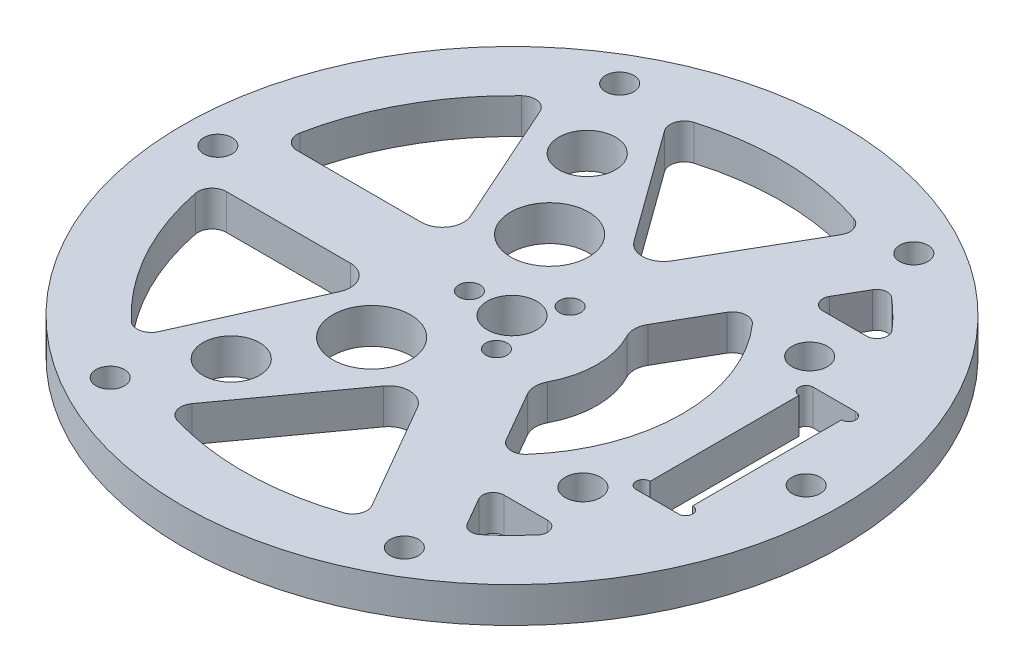
SolidWorks part; units mm, degrees
material "Thornel Mat VMA"
ref_plane "前视基准面" through (0, 0, 0) normal (0, 0, 1) x (1, 0, 0)
ref_plane "上视基准面" through (0, 0, 0) normal (0, 1, 0) x (1, 0, 0)
ref_plane "右视基准面" through (0, 0, 0) normal (1, 0, 0) x (0, 0, -1)
sketch "草图1" plane through (0, 0, 0) normal (0, 1, 0) x (1, 0, 0)
  line L7 (0, 0) -> (36, 0) construction
  line L8 (26, 16) -> (26, -16) construction
  line L11 (30, 12.5) -> (30, -12.5)
  line L12 (30, -12.5) -> (36, -12.5)
  line L13 (36, -12.5) -> (36, 12.5)
  line L14 (36, 12.5) -> (30, 12.5)
  circle A0 centre (0, 0) radius 41.5 construction
  circle A1 centre (0, 0) radius 46.5
  circle A2 centre (-20.75, 35.9401) radius 2
  circle A3 centre (20.75, 35.9401) radius 2
  circle A4 centre (41.5, 0) radius 2
  circle A5 centre (20.75, -35.9401) radius 2
  circle A6 centre (0, 0) radius 3.5
  circle A7 centre (-20.75, -35.9401) radius 2
  circle A8 centre (-41.5, 0) radius 2
  circle A9 centre (26, 16) radius 2.5
  circle A10 centre (26, -16) radius 2.5
  circle A12 centre (-14.5, 25.1147) radius 4
  circle A13 centre (0, 0) radius 6 construction
  circle A14 centre (-6, 0) radius 1.5
  circle A15 centre (3, 5.1962) radius 1.5
  circle A16 centre (29, 0) radius 4 construction
  circle A17 centre (3, -5.1962) radius 1.5
  circle A18 centre (-14.5, -25.1147) radius 4
  circle A19 centre (0, 0) radius 29 construction
  point P24 (26, 0)
  dimension "D1" = 5
  dimension "D2" = 4
  dimension "D3" = 83
  dimension "D4" = 6
  dimension "D9" = 5
  dimension "D11" = 7
  dimension "D12" = 12
  dimension "D13" = 3
  dimension "D15" = 58
  dimension "D16" = 8
  dimension "D6" = 25
  dimension "D7" = 30
  dimension "D8" = 4
  dimension "D10" = 32
  dimension "D5" = 6
  dimension "D14" = 3
extrude "凸台-拉伸1" add sketch "草图1" along normal blind 5
hole_wizard "孔1" positions "草图2" profile "草图3" legacy end condition through all
sketch "草图2" plane through (0, 0, 0) normal (0, -1, 0) x (-1, 0, 0)
  point P2 (-3, 5.1962)
  point P11 (6, 0)
  point P12 (-3, -5.1962)
  point P14 (6, -0.4384)
  point P15 (6, 0)
  dimension "D1" = 3
sketch "草图3" plane through (3, 0, -5.1962) normal (1, 0, 0) x (0, 0, -1)
  line L0 (0, 0) -> (0, 5)
  line L1 (0, 5) -> (1.5, 5)
  line L2 (1.5, 5) -> (1.5, 1.5)
  line L3 (1.5, 1.5) -> (3, 0)
  line L4 (3, 0) -> (0, 0)
  line L5 (0, -6.4453) -> (0, 115.525) construction
  line L6 (-1.5, 1.5) -> (-3, 0) construction
  dimension "直径" = 3
  dimension "深度" = 5
  dimension "锥坑角度" = 90
  dimension "锥坑直径" = 6
hole_wizard "孔2" positions "草图6" profile "草图7" legacy end condition through all
sketch "草图6" plane through (0, 0, 0) normal (0, -1, 0) x (-1, 0, 0)
  point P0 (-41.5, 0)
  point P7 (-20.75, 35.9401)
  point P8 (20.75, 35.9401)
  point P9 (41.5, 0)
  point P10 (20.75, -35.9401)
  point P11 (-20.75, -35.9401)
  point P13 (-20.75, 35.9401)
  dimension "D1" = 6
sketch "草图7" plane through (41.5, 0, 0) normal (1, 0, 0) x (0, 0, -1)
  line L0 (0, 0) -> (0, 5)
  line L1 (0, 5) -> (2, 5)
  line L2 (2, 5) -> (2, 2)
  line L3 (2, 2) -> (4, 0)
  line L4 (4, 0) -> (0, 0)
  line L5 (0, -6.4453) -> (0, 115.525) construction
  line L6 (-2, 2) -> (-4, 0) construction
  dimension "直径" = 4
  dimension "深度" = 5
  dimension "锥坑角度" = 90
  dimension "锥坑直径" = 8
sketch "草图4" plane through (0, 5, 0) normal (0, 1, 0) x (1, 0, 0)
  line L0 (30, 12.5) -> (30, -12.5) construction
  line L1 (36, -12.5) -> (36, 12.5) construction
  circle A0 centre (30, 11.5) radius 1
  circle A1 centre (30, -11.5) radius 1
  circle A2 centre (36, -11.5) radius 1
  circle A3 centre (36, 11.5) radius 1
  dimension "D1" = 2
extrude "切除-拉伸1" cut sketch "草图4" against normal through all
sketch "草图5" plane through (0, 0, 0) normal (0, -1, 0) x (1, 0, 0)
  line L0 (-24.0786, 29.3976) -> (-13.1843, 5)
  line L1 (-13.1843, 5) -> (-37.6696, 5)
  line L2 (2.262, 13.918) -> (14.5047, 35.1228)
  line L3 (0, 0) -> (-20.75, 35.9401) construction
  line L4 (-13.4198, 35.5515) -> (2.262, 13.918)
  line L5 (0, 0) -> (20.75, 35.9401) construction
  line L6 (16.0815, 17.8539) -> (9.7845, 6.9472)
  line L7 (23.1649, 30.1228) -> (18.7639, 22.5)
  line L8 (18.7639, 22.5) -> (30.6227, 22.5)
  line L9 (2.75, 0) -> (-2.75, 0) construction
  line L10 (16.0815, -17.8539) -> (9.7845, -6.9472)
  line L11 (18.7639, -22.5) -> (30.6227, -22.5)
  line L12 (23.1649, -30.1228) -> (18.7639, -22.5)
  line L13 (2.262, -13.918) -> (14.5047, -35.1228)
  line L14 (-13.4198, -35.5515) -> (2.262, -13.918)
  line L15 (-13.1843, -5) -> (-37.6696, -5)
  line L16 (-24.0786, -29.3976) -> (-13.1843, -5)
  circle A0 centre (-7.25, 12.5574) radius 5.5
  circle A1 centre (0, 0) radius 9 construction
  circle A3 centre (-14.5, 25.1147) radius 9 construction
  circle A4 centre (-14.5, 25.1147) radius 4 construction
  circle A5 centre (-7.25, 12.5574) radius 8.5 construction
  circle A6 centre (-14.5, 25.1147) radius 7 construction
  arc A7 (-24.0786, 29.3976) -> (-37.6696, 5) centre (0, 0) ccw
  circle A8 centre (-41.5, 0) radius 2 construction
  circle A9 centre (0, 0) radius 46.5 construction
  arc A10 (-13.4198, 35.5515) -> (14.5047, 35.1228) centre (0, 0) cw
  arc A11 (16.0815, -17.8539) -> (16.0815, 17.8539) centre (0, 0) ccw
  circle A12 centre (26, 16) radius 6.5 construction
  circle A13 centre (26, 16) radius 2.5 construction
  arc A14 (9.7845, -6.9472) -> (9.7845, 6.9472) centre (0, 0) ccw
  arc A15 (23.1649, 30.1228) -> (30.6227, 22.5) centre (0, 0) cw
  arc A16 (23.1649, -30.1228) -> (30.6227, -22.5) centre (0, 0) ccw
  arc A17 (-13.4198, -35.5515) -> (14.5047, -35.1228) centre (0, 0) ccw
  circle A18 centre (-7.25, -12.5574) radius 5.5
  arc A19 (-24.0786, -29.3976) -> (-37.6696, -5) centre (0, 0) cw
  arc A20 (-3.2708, 1.2457) -> (-3.2708, -1.2457) centre (-6, 0) ccw construction
  dimension "D1" = 5
  dimension "D2" = 3
  dimension "D3" = 3
  dimension "D4" = 5
  dimension "D5" = 8.5
  dimension "D6" = 4
  dimension "D8" = 3
  dimension "D7" = 5
extrude "切除-拉伸2" cut sketch "草图5" against normal through all
fillet "圆角1" radius 2 10 edges at (14.5047, 2.5, -35.1228) (-13.4198, 2.5, -35.5515) (-37.6696, 2.5, -5) (-24.0786, 2.5, -29.3976) (-37.6696, 2.5, 5) (-24.0786, 2.5, 29.3976) (-13.4198, 2.5, 35.5515) (14.5047, 2.5, 35.1228) (16.0815, 2.5, -17.8539) (16.0815, 2.5, 17.8539)
fillet "圆角2" radius 3 6 edges at (9.7845, 2.5, 6.9472) (9.7845, 2.5, -6.9472) (2.262, 2.5, -13.918) (-13.1843, 2.5, -5) (-13.1843, 2.5, 5) (2.262, 2.5, 13.918)
fillet "圆角3" radius 1.5 6 edges at (18.7639, 2.5, -22.5) (23.1649, 2.5, -30.1228) (30.6227, 2.5, -22.5) (30.6227, 2.5, 22.5) (18.7639, 2.5, 22.5) (23.1649, 2.5, 30.1228)
